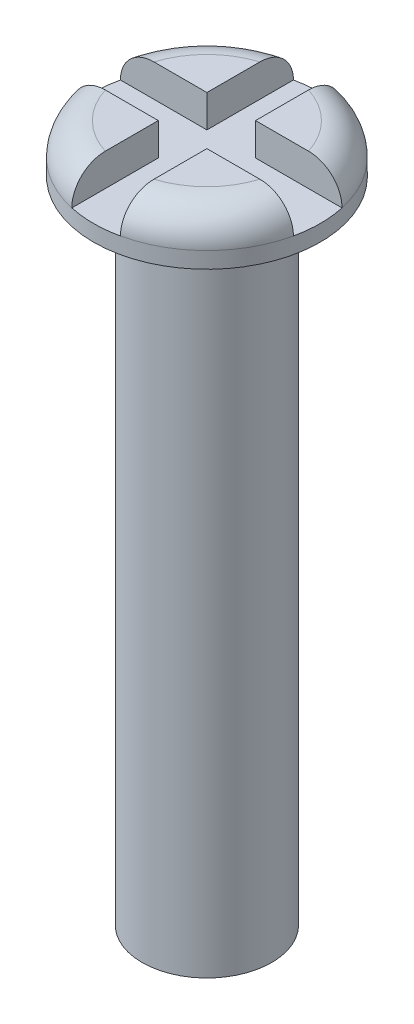
SolidWorks part; units mm, degrees
ref_plane "前视基准面" through (0, 0, 0) normal (0, 0, 1) x (1, 0, 0)
ref_plane "上视基准面" through (0, 0, 0) normal (0, 1, 0) x (1, 0, 0)
ref_plane "右视基准面" through (0, 0, 0) normal (1, 0, 0) x (0, 0, -1)
sketch "草图1" plane through (0, 0, 0) normal (0, 1, 0) x (1, 0, 0)
  circle A0 centre (0, 0) radius 1
  dimension "D1" = 2
extrude "拉伸1" add sketch "草图1" along normal blind 10
sketch "草图2" plane through (0, 10, 0) normal (0, 1, 0) x (-1, 0, 0)
  circle A0 centre (0, 0) radius 1.75
  dimension "D1" = 3.5
extrude "拉伸2" add sketch "草图2" along normal blind 0.75
fillet "圆角1" radius 0.5 1 edges at (0, 10.75, 1.75)
sketch "草图3" plane through (0, 10.75, 0) normal (0, 1, 0) x (-1, 0, 0)
  line L0 (4.0624, 0) -> (-4.2778, 0) construction
  line L1 (0, -3.5166) -> (0, 3.738) construction
  line L3 (3.5023, -0.375) -> (-3.5023, -0.375)
  line L4 (3.5023, -0.375) -> (3.5023, 0.375)
  line L5 (3.5023, 0.375) -> (-3.5023, 0.375)
  line L6 (-3.5023, -0.375) -> (-3.5023, 0.375)
  dimension "D1" = 0.75
extrude "切除-拉伸1" cut sketch "草图3" against normal blind 0.5
sketch "草图4" plane through (0, 10.75, 0) normal (0, 1, 0) x (-1, 0, 0)
  line L0 (0, -3.8639) -> (0, 3.6765) construction
  line L1 (1.7727, 0) -> (-1.7019, 0) construction
  line L2 (0.375, -1.875) -> (-0.375, -1.875)
  line L3 (0.375, -1.875) -> (0.375, 1.875)
  line L4 (0.375, 1.875) -> (-0.375, 1.875)
  line L5 (-0.375, -1.875) -> (-0.375, 1.875)
  dimension "D1" = 0.75
  dimension "D2" = 3.75
extrude "切除-拉伸2" cut sketch "草图4" against normal blind 0.5
